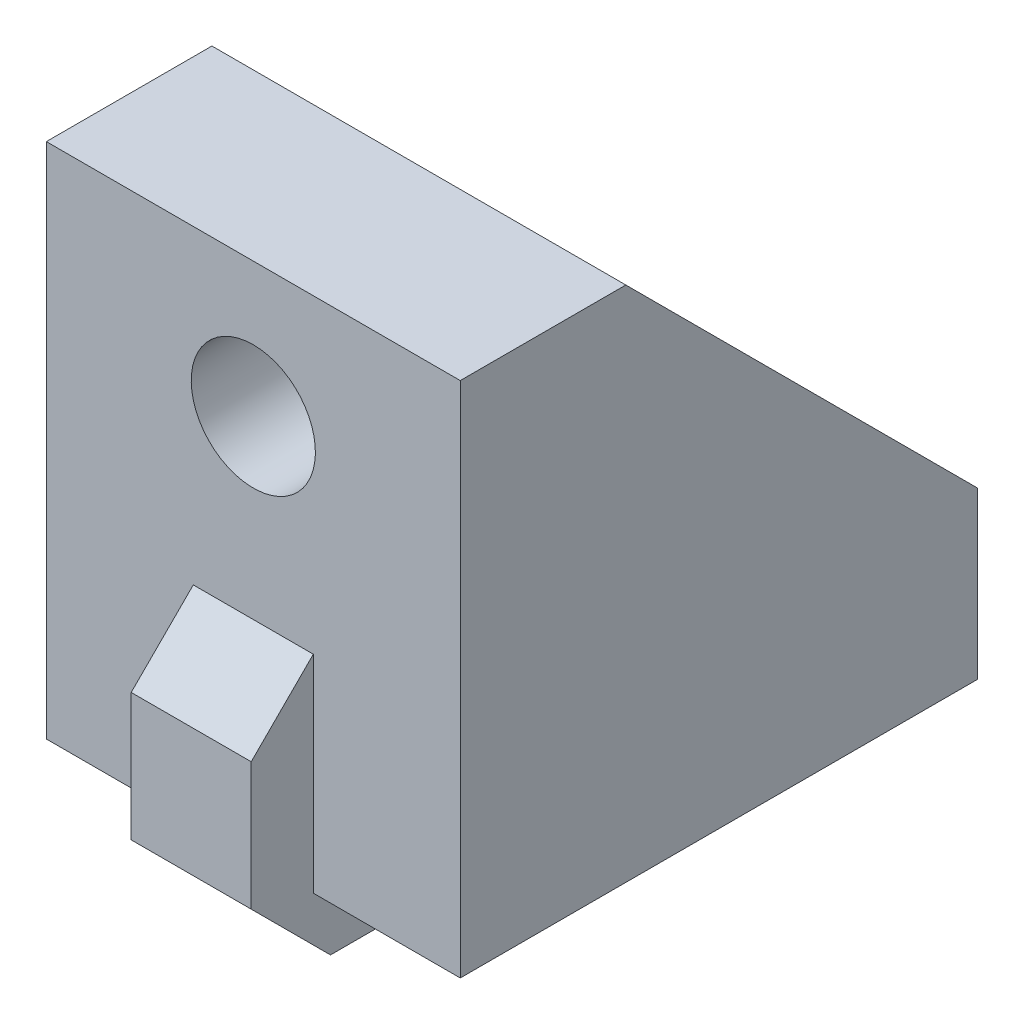
SolidWorks part; units mm, degrees
ref_plane "Front Plane" through (0, 0, 0) normal (0, 0, 1) x (1, 0, 0)
ref_plane "Top Plane" through (0, 0, 0) normal (0, 1, 0) x (1, 0, 0)
ref_plane "Right Plane" through (0, 0, 0) normal (1, 0, 0) x (0, 0, -1)
sketch "Sketch2" plane through (0, 0, 0) normal (1, 0, 0) x (0, 0, -1)
  line L0 (0, 0) -> (-20, -20) construction
  line L1 (-20, 5) -> (-12, 5)
  line L2 (-20, 5) -> (-20, -20)
  line L3 (-20, -20) -> (5, -20)
  line L4 (5, -12) -> (5, -20)
  line L7 (-12, 5) -> (-12, -12)
  line L8 (-12, -12) -> (5, -12)
  dimension "D1" = 8
  dimension "D2" = 25
  dimension "D3" = 25
extrude "Boss-Extrude1" add sketch "Sketch2" along normal mid plane 20
sketch "Sketch15" plane through (10, 0, 0) normal (1, 0, 0) x (0, 0, -1)
  line L0 (-12, 5) -> (5, -12)
rib "Rib18" sketch "Sketch15" sketch "Sketch15" thickness 4.5 extrusion direction parallel to sketch draft on no parameters "D1"=4.5
sketch "Sketch17" plane through (-10, 0, 0) normal (-1, 0, 0) x (0, 0, 1)
  line L0 (12, 5) -> (-5, -12)
rib "Rib38" sketch "Sketch17" sketch "Sketch17" thickness 4.5 extrusion direction parallel to sketch draft on no parameters "D1"=4.5
sketch "Sketch31" plane through (0, 0, 0) normal (1, 0, 0) x (0, 0, -1)
  line L0 (-20, -10) -> (-20, -20)
  line L1 (-23, -13) -> (-23, -19.1708)
  line L2 (-19.1708, -23) -> (-13, -23)
  line L5 (-20, -20) -> (-10, -20)
  line L6 (-20, -20) -> (5, -20) construction
  line L7 (-20, 5) -> (-20, -20) construction
  line L8 (-20, -10) -> (-23, -13)
  line L9 (-10, -20) -> (-13, -23)
  line L12 (-23, -19.1708) -> (-19.1708, -23)
  dimension "D1" = 10
  dimension "D2" = 3
extrude "Boss-Extrude2" add sketch "Sketch31" along normal mid plane 5.8
sketch "Sketch36" plane through (0, 0, 12) normal (0, 0, -1) x (-1, 0, 0)
  circle A0 centre (0, -1.5) radius 5.25
  dimension "D1" = 10.5
extrude "Cut-Extrude4" cut sketch "Sketch36" against normal blind 1
sketch "Sketch37" plane through (0, 0, 13) normal (0, 0, -1) x (-1, 0, 0)
  circle A0 centre (0, -1.5) radius 3
  dimension "D1" = 6
extrude "Cut-Extrude5" cut sketch "Sketch37" against normal blind 8
sketch "Sketch33" plane through (0, -12, 0) normal (0, 1, 0) x (1, 0, 0)
  circle A0 centre (0, -1.5) radius 5.25
  dimension "D1" = 10.5
extrude "Cut-Extrude1" cut sketch "Sketch33" against normal blind 1
sketch "Sketch38" plane through (0, -13, 0) normal (0, 1, 0) x (1, 0, 0)
  circle A0 centre (0, -1.5) radius 3
  dimension "D1" = 6
extrude "Cut-Extrude6" cut sketch "Sketch38" against normal blind 8
